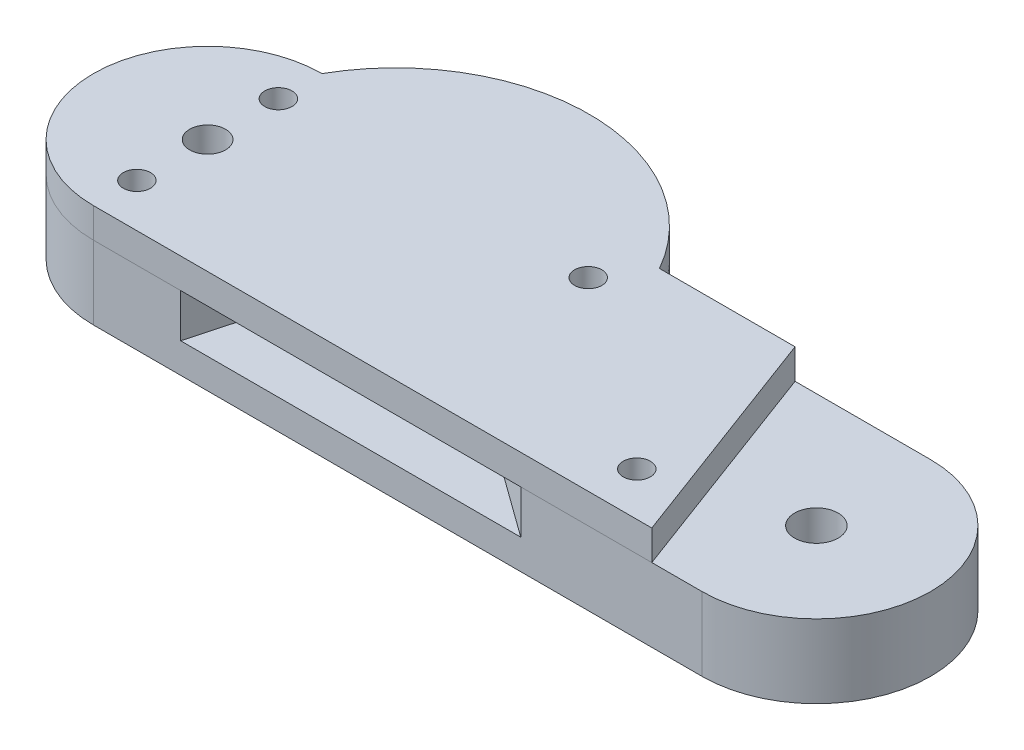
SolidWorks part; units mm, degrees
ref_plane "Front Plane" through (0, 0, 0) normal (0, 0, 1) x (1, 0, 0)
ref_plane "Top Plane" through (0, 0, 0) normal (0, 1, 0) x (1, 0, 0)
ref_plane "Right Plane" through (0, 0, 0) normal (1, 0, 0) x (0, 0, -1)
sketch "Sketch1" plane through (0, 0, 0) normal (0, 1, 0) x (1, 0, 0)
  line L0 (0, -10.5004) -> (-55.9305, -10.5004)
  line L1 (0, 10.5004) -> (-55.9305, 10.5004)
  line L5 (0, 11.5004) -> (-55.9305, 11.5004) construction
  line L6 (0, -11.5004) -> (-55.9305, -11.5004) construction
  circle A0 centre (0, 0) radius 2
  arc A1 (0, -10.5004) -> (0, 10.5004) centre (0, 0) ccw
  arc A2 (-55.9305, 10.5004) -> (-55.9305, -10.5004) centre (-55.9305, 0) ccw
  circle A3 centre (-55.9305, 0) radius 1.65
  arc A7 (0, -11.5004) -> (0, 11.5004) centre (0, 0) ccw construction
  arc A8 (-55.9305, 11.5004) -> (-55.9305, -11.5004) centre (-55.9305, 0) ccw construction
  arc A9 (-67.2423, -5.04) -> (-54.9145, -15.6487) centre (-55.7741, -4.1805) ccw construction
  arc A10 (-55.9305, 10.5004) -> (-55.9305, -10.5004) centre (-55.9305, 0) ccw construction
  dimension "D1" = 4
  dimension "D2" = 1
  dimension "D3" = 3.3
  dimension "D4" = 55.9305
extrude "Boss-Extrude1" add sketch "Sketch1" along normal mid plane 9.5
sketch "Sketch3" plane through (0, 0, 0) normal (0, 1, 0) x (1, 0, 0)
  line L0 (0, 0) -> (-47.1525, -15.3208) construction
  line L1 (0, 0) -> (24.7895, -42.9367) construction
  line L2 (0, 0) -> (-55.9305, 0) construction
  line L3 (24.7895, -42.9367) -> (-41.5934, 5.0595) construction
  line L4 (-41.5934, 5.0595) -> (-47.1525, -15.3208) construction
  line L5 (-41.5934, 5.0595) -> (-37.6461, 19.5308) construction
  line L6 (-41.5934, 5.0595) -> (-53.749, 13.8482) construction
  line L7 (22.8477, -44.0007) -> (-38.0092, 0) construction
  line L8 (-35.7518, 18.8753) -> (-39.2995, 5.869)
  line L9 (-43.8873, 4.25) -> (-54.8123, 12.149)
  line L11 (26.6452, -41.8104) -> (-39.2995, 5.869)
  line L12 (-39.6108, 19.9279) -> (-42.7627, 8.3729) construction
  line L13 (-42.7627, 8.3729) -> (-52.4686, 15.3905) construction
  line L14 (-40.9004, 0) -> (-45.9674, -18.5763) construction
  line L15 (-43.8873, 4.25) -> (-48.2065, -11.585)
  line L18 (-40.4216, 6.6802) -> (-50.8477, 14.2185) construction
  line L20 (-41.5934, 5.0595) -> (-52.0196, 12.5978) construction
  line L21 (-42.7652, 3.4387) -> (-53.1914, 10.977) construction
  line L23 (-43.5229, 5.5858) -> (-49.082, -14.7945) construction
  line L26 (-39.6639, 4.5332) -> (-45.223, -15.8471) construction
  line L27 (25.9613, -41.316) -> (-40.4216, 6.6802) construction
  line L28 (23.6177, -44.5574) -> (-42.7652, 3.4387) construction
  arc A1 (-48.2065, -11.585) -> (26.6452, -41.8104) centre (0, 0) ccw
  arc A4 (-55.9305, 10.5004) -> (-55.9305, -10.5004) centre (-55.9305, 0) ccw construction
  arc A7 (-35.7518, 18.8753) -> (-54.8123, 12.149) centre (-41.5934, 5.0595) ccw
  dimension "D1" = 99.1581
  dimension "D3" = 120
  dimension "D6" = 30
  dimension "D2" = 18
  dimension "D4" = 2
  dimension "D5" = 2
extrude "Cut-Extrude1" cut sketch "Sketch3" against normal mid plane 4
sketch "Sketch5" plane through (0, 0, 0) normal (0, 1, 0) x (1, 0, 0)
  line L0 (-40.4241, 1.7461) -> (-52.5322, 10.5004) construction
  line L1 (-40.4241, 1.7461) -> (-35.7382, 18.9254) construction
  line L2 (-52.5322, 10.5004) -> (-43.8873, 4.25) construction
  line L3 (-39.2995, 5.869) -> (-38.0362, 10.5004) construction
  line L4 (-55.9305, 10.5004) -> (-24.9177, 10.5004)
  line L5 (0, 10.5004) -> (-55.9305, 10.5004) construction
  circle A0 centre (-40.4241, 1.7461) radius 17.807
extrude "Boss-Extrude2" add sketch "Sketch5" along normal up to surface and the other way up to surface
sketch "Sketch6" plane through (0, 0, 0) normal (0, 1, 0) x (1, 0, 0)
  line L0 (-39.2995, 5.869) -> (-16.6593, -10.5004)
  line L1 (-47.9107, -10.5004) -> (-43.8873, 4.25)
  line L2 (-43.8873, 4.25) -> (-54.8544, 12.1794)
  line L3 (-39.2995, 5.869) -> (-35.7382, 18.9254)
  line L4 (-16.6593, -10.5004) -> (-39.2995, 5.869) construction
  line L5 (-43.8873, 4.25) -> (-47.9107, -10.5004) construction
  line L6 (-52.5322, 10.5004) -> (-43.8873, 4.25) construction
  line L7 (-39.2995, 5.869) -> (-38.0362, 10.5004) construction
  line L8 (-55.9305, -10.5004) -> (0, -10.5004) construction
  line L9 (-16.6593, -10.5004) -> (-47.9107, -10.5004)
  arc A0 (-24.9177, 10.5004) -> (-55.9305, 10.5004) centre (-40.4241, 1.7461) ccw construction
  arc A1 (-35.7382, 18.9254) -> (-54.8544, 12.1794) centre (-40.4241, 1.7461) ccw
extrude "Cut-Extrude2" cut sketch "Sketch6" against normal mid plane 4
sketch "Sketch7" plane through (0, -4.75, 0) normal (0, -1, 0) x (1, 0, 0)
  line L0 (0, 0) -> (4.5965, 4.5965) construction
  line L1 (0, 0) -> (6.5004, 0) construction
  line L4 (0, 6.5004) -> (-55.9305, 6.5004)
  line L5 (-27.4616, -6.5004) -> (0, -6.5004)
  line L6 (0, 6.5004) -> (-55.9305, 6.5004) construction
  line L7 (-55.9305, -6.5004) -> (0, -6.5004) construction
  circle A3 centre (-27.4616, -6.5004) radius 1.25
  circle A4 centre (0, -6.5004) radius 1.25 construction
  circle A5 centre (4.5965, 4.5965) radius 1.25 construction
  arc A6 (0, -6.5004) -> (0, 6.5004) centre (0, 0) ccw
  arc A7 (-55.9305, 6.5004) -> (-53.5442, -6.0466) centre (-55.9305, 0) ccw
  arc A8 (-53.5442, -6.0466) -> (-27.4616, -6.5004) centre (-40.4241, -1.7461) ccw
  arc A9 (0, -6.5004) -> (0, 6.5004) centre (0, 0) ccw construction
  arc A10 (-55.9305, 6.5004) -> (-53.5442, -6.0466) centre (-55.9305, 0) ccw construction
  arc A11 (-53.5442, -6.0466) -> (-27.4616, -6.5004) centre (-40.4241, -1.7461) ccw construction
  circle A12 centre (-10, 6.5004) radius 1.25
  circle A13 centre (-55.9305, 6.5004) radius 1.25
  circle A14 centre (-55.9305, -6.5004) radius 1.25
  dimension "D4" = 2.5
  dimension "D2" = 10
  dimension "D3" = 45
  dimension "D1" = 4
extrude "Cut-Extrude3" cut sketch "Sketch7" against normal through all
sketch "Sketch8" plane through (0, -4.75, 0) normal (0, -1, 0) x (1, 0, 0)
  circle A0 centre (-55.9305, 6.5004) radius 2.75
  circle A1 centre (-55.9305, -6.5004) radius 2.75
  circle A2 centre (-27.4616, -6.5004) radius 2.75
  circle A3 centre (-10, 6.5004) radius 2.75
  dimension "D1" = 5.5
extrude "Cut-Extrude4" cut sketch "Sketch8" against normal blind 3.2
ref_plane "Plane1" through (0, 2, 0) normal (0, -1, 0) x (-1, 0, 0)
sketch "Sketch9" plane through (0, 4.75, 0) normal (0, 1, 0) x (1, 0, 0)
  line L0 (-12.4589, 10.5004) -> (-4.6195, -10.5004)
  line L1 (0, 10.5004) -> (-24.9177, 10.5004) construction
  line L2 (-55.9305, -10.5004) -> (0, -10.5004) construction
  line L3 (-6.5881, -5.2268) -> (-10, -6.5004) construction
  line L4 (-4.6195, -10.5004) -> (0, -10.5004)
  line L5 (-12.4589, 10.5004) -> (0, 10.5004)
  circle A0 centre (0, 0) radius 8 construction
  circle A1 centre (-10, -6.5004) radius 1.25 construction
  circle A2 centre (-10, -6.5004) radius 1.25 construction
  arc A3 (0, -10.5004) -> (0, 10.5004) centre (0, 0) ccw
  arc A4 (0, -10.5004) -> (0, 10.5004) centre (0, 0) ccw construction
  dimension "D1" = 16
extrude "Cut-Extrude5" cut sketch "Sketch9" against normal up to surface (2.75 mm away)
split "Split1" trim tools "Plane1" bodies to split 113 resulting bodies 111 112
